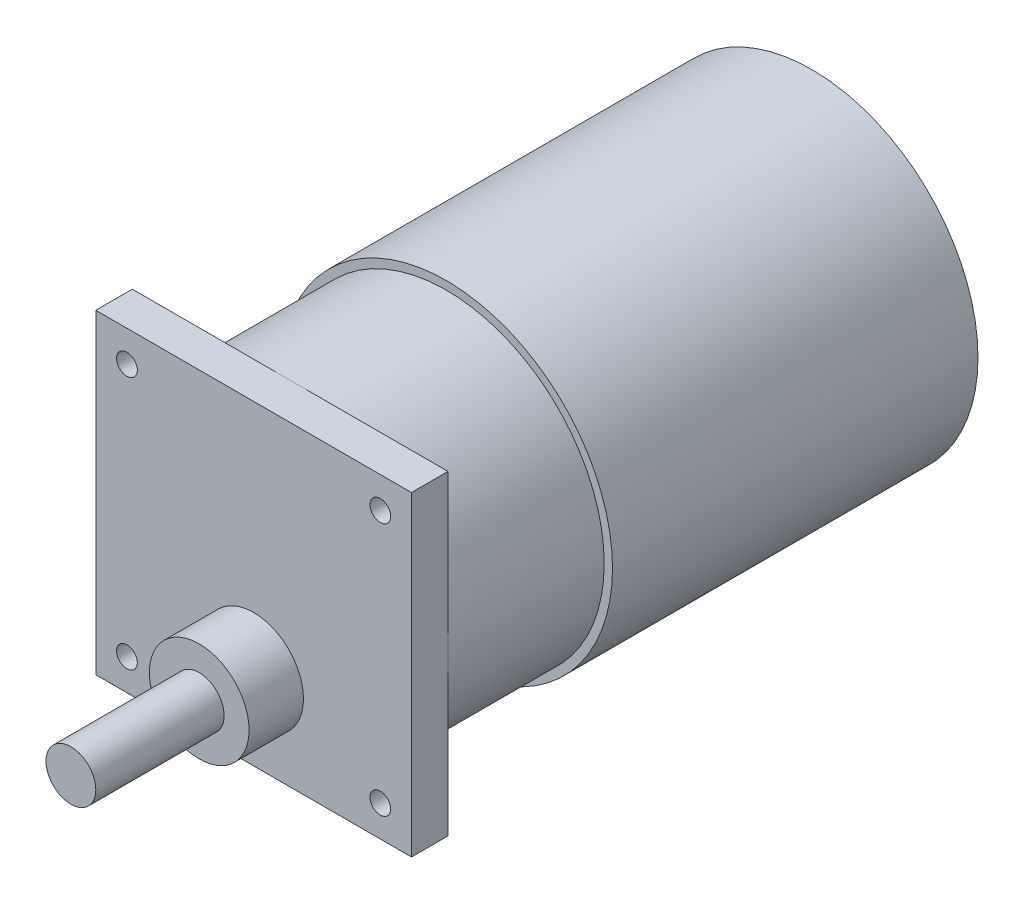
SolidWorks part; units mm, degrees
ref_plane "Plan de face" through (0, 0, 0) normal (0, 0, 1) x (1, 0, 0)
ref_plane "Plan de dessus" through (0, 0, 0) normal (0, 1, 0) x (1, 0, 0)
ref_plane "Plan de droite" through (0, 0, 0) normal (1, 0, 0) x (0, 0, -1)
sketch "Esquisse1" plane through (0, 0, 0) normal (0, 0, 1) x (1, 0, 0)
  circle A0 centre (0, 0) radius 20
extrude "Extrusion1" add sketch "Esquisse1" along normal blind 44
sketch "Esquisse2" plane through (0, 0, 44) normal (0, 0, 1) x (1, 0, 0)
  circle A0 centre (0, 0) radius 19
extrude "Extrusion2" add sketch "Esquisse2" along normal blind 18.8
sketch "Esquisse3" plane through (0, 0, 62.8) normal (0, 0, 1) x (1, 0, 0)
  line L1 (-19, 19) -> (19, 19)
  line L2 (-19, 19) -> (-19, -19)
  line L3 (-19, -19) -> (19, -19)
  line L4 (19, 19) -> (19, -19)
extrude "Extrusion3" add sketch "Esquisse3" along normal blind 4.4
sketch "Esquisse4" plane through (0, 0, 67.2) normal (0, 0, 1) x (1, 0, 0)
  line L0 (19, 19) -> (-19, 19) construction
  line L1 (-15.25, 15.25) -> (15.25, 15.25) construction
  line L2 (-15.25, 15.25) -> (-15.25, -15.25) construction
  line L3 (-15.25, -15.25) -> (15.25, -15.25) construction
  line L4 (15.25, 15.25) -> (15.25, -15.25) construction
  line L5 (-19, 19) -> (-19, -19) construction
  circle A0 centre (-15.25, 15.25) radius 1.25
  circle A1 centre (15.25, 15.25) radius 1.25
  circle A2 centre (15.25, -15.25) radius 1.25
  circle A3 centre (-15.25, -15.25) radius 1.25
  dimension "D1" = 30.5
  dimension "D2" = 30.5
  dimension "D3" = 3.75
  dimension "D4" = 3.75
extrude "Extrusion4" cut sketch "Esquisse4" against normal through all
sketch "Esquisse5" plane through (0, 0, 67.2) normal (0, 0, 1) x (1, 0, 0)
  line L0 (0, 0) -> (-12.9531, 0) construction
  circle A0 centre (0, -9) radius 6
  dimension "D1" = 9
extrude "Extrusion5" add sketch "Esquisse5" along normal blind 6.55
sketch "Esquisse6" plane through (0, 0, 73.75) normal (0, 0, 1) x (1, 0, 0)
  line L0 (-2.6192, -9) -> (3.0954, -9) construction
  circle A0 centre (0, -9) radius 3
  dimension "D1" = 9
extrude "Extrusion6" add sketch "Esquisse6" along normal blind 15.45
